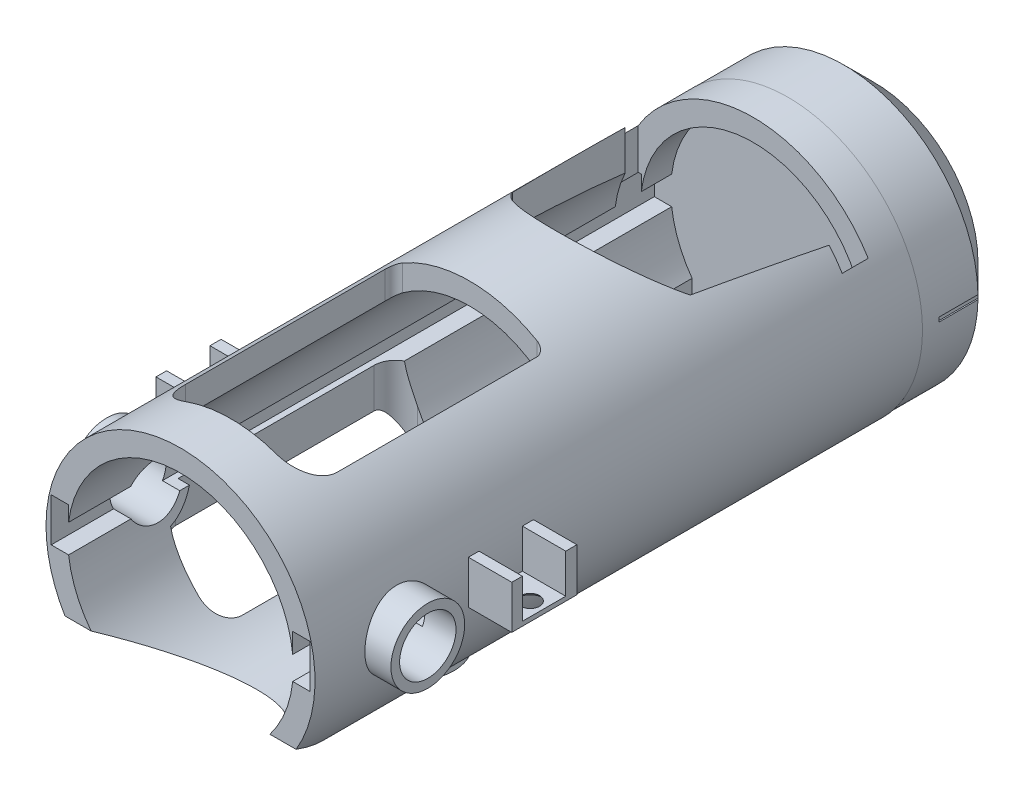
SolidWorks part; units mm, degrees
material "PET"
ref_plane "Front Plane" through (0, 0, 0) normal (0, 0, 1) x (1, 0, 0)
ref_plane "Top Plane" through (0, 0, 0) normal (0, 1, 0) x (1, 0, 0)
ref_plane "Right Plane" through (0, 0, 0) normal (1, 0, 0) x (0, 0, -1)
sketch "Sketch1" plane through (0, 0, 0) normal (0, 0, 1) x (1, 0, 0)
  circle A0 centre (0, 0) radius 31
  dimension "D1" = 62
extrude "Boss-Extrude1" add sketch "Sketch1" along normal blind 140
sketch "Sketch3" plane through (0, 0, 0) normal (0, 1, 0) x (1, 0, 0)
  line L0 (31, 0) -> (-31, 0) construction
  line L1 (-21.0968, 0) -> (20.9032, 0)
  line L2 (-21.0968, 0) -> (-21.0968, -42)
  line L3 (-11.0968, -52) -> (10.9032, -52)
  line L4 (20.9032, 0) -> (20.9032, -42)
  line L5 (-21.0968, 0) -> (20.9032, -52) construction
  line L6 (-21.0968, -52) -> (20.9032, 0) construction
  arc A0 (10.9032, -52) -> (20.9032, -42) centre (10.9032, -42) ccw
  arc A1 (-21.0968, -42) -> (-11.0968, -52) centre (-11.0968, -42) ccw
  point P0 (-0.0968, -26)
  dimension "D3" = 10
  dimension "D1" = 42
  dimension "D2" = 42
extrude "Cut-Extrude3" cut sketch "Sketch3" against normal blind 160
sketch "Sketch4" plane through (0, 0, 0) normal (0, 1, 0) x (1, 0, 0)
  line L0 (10.9032, -52) -> (-11.0968, -52) construction
  circle A0 centre (0, -87) radius 10
  dimension "D1" = 35
extrude "Boss-Extrude2" add sketch "Sketch4" against normal blind 35
sketch "Sketch5" plane through (0, -35, 0) normal (0, -1, 0) x (1, 0, 0)
  circle A0 centre (0, 87) radius 9
extrude "Cut-Extrude4" cut sketch "Sketch5" against normal blind 49
sketch "Sketch6" plane through (0, 0, 0) normal (0, 1, 0) x (1, 0, 0)
  line L1 (-23.4267, -117.7734) -> (-18, -117.7734)
  line L2 (-28.4267, -112.7734) -> (-28.4267, -67)
  line L3 (-23.4267, -62) -> (-18, -62)
  line L4 (-13, -112.7734) -> (-13, -67)
  line L5 (-28.4267, -117.7734) -> (-13, -62) construction
  line L6 (-28.4267, -62) -> (-13, -117.7734) construction
  circle A0 centre (0, -87) radius 10 construction
  arc A1 (-28.4267, -67) -> (-23.4267, -62) centre (-23.4267, -67) cw
  arc A2 (-18, -62) -> (-13, -67) centre (-18, -67) cw
  arc A3 (-18, -117.7734) -> (-13, -112.7734) centre (-18, -112.7734) ccw
  arc A4 (-23.4267, -117.7734) -> (-28.4267, -112.7734) centre (-23.4267, -112.7734) cw
  point P0 (-20.7133, -89.8867)
  dimension "D3" = 5
  dimension "D1" = 13
  dimension "D2" = 10
extrude "Cut-Extrude5" cut sketch "Sketch6" against normal blind 49
sketch "Sketch7" plane through (0, 0, 0) normal (0, 1, 0) x (1, 0, 0)
  line L1 (-15.5, -73.3534) -> (15.5, -73.3534)
  line L2 (-17.5, -75.3534) -> (-17.5, -121.3534)
  line L3 (-10.5, -128.3534) -> (10.5, -128.3534)
  line L4 (17.5, -75.3534) -> (17.5, -121.3534)
  line L5 (-17.5, -73.3534) -> (17.5, -128.3534) construction
  line L6 (-17.5, -128.3534) -> (17.5, -73.3534) construction
  arc A0 (10.5, -128.3534) -> (17.5, -121.3534) centre (10.5, -121.3534) ccw
  arc A1 (-17.5, -121.3534) -> (-10.5, -128.3534) centre (-10.5, -121.3534) ccw
  arc A2 (15.5, -73.3534) -> (17.5, -75.3534) centre (15.5, -75.3534) cw
  arc A3 (-15.5, -73.3534) -> (-17.5, -75.3534) centre (-15.5, -75.3534) ccw
  point P0 (0, -100.8534)
  dimension "D2" = 7
  dimension "D3" = 2
  dimension "D1" = 35
  dimension "D4" = 55
  dimension "D5" = 35
extrude "Cut-Extrude6" cut sketch "Sketch7" along normal blind 100
sketch "Sketch8" plane through (0, 0, 0) normal (0, 1, 0) x (1, 0, 0)
  line L0 (-26.5, -8) -> (26.5, -8)
  line L1 (26.5, -8) -> (26.5, -14)
  line L2 (26.5, -14) -> (23.5, -14)
  line L3 (23.5, -14) -> (20.5, -43)
  line L4 (-20.5, -43) -> (-23.5, -14)
  line L5 (-23.5, -14) -> (-26.5, -14)
  line L6 (-26.5, -14) -> (-26.5, -8)
  line L7 (31, 0) -> (-31, 0) construction
  arc A0 (20.5, -43) -> (-20.5, -43) centre (0, -28) cw
  point P3 (0, -8)
  dimension "D1" = 3
  dimension "D2" = 3
  dimension "D3" = 6
  dimension "D4" = 8
  dimension "D5" = 53
  dimension "D6" = 41
  dimension "D7" = 20
  dimension "D8" = 29
  dimension "D9" = 29
  dimension "D10" = 6
extrude "Cut-Extrude7" cut sketch "Sketch8" along normal blind 77
sketch "Sketch11" plane through (0, 0, 0) normal (1, 0, 0) x (0, 0, -1)
  line L0 (-140, 31) -> (-140, -31) construction
  circle A0 centre (-120, 0) radius 8.5
  dimension "D1" = 20
  dimension "D2" = 17
extrude "Boss-Extrude3" add sketch "Sketch11" against normal blind 37 and the other way blind 37
sketch "Sketch12" plane through (-37, 0, 0) normal (-1, 0, 0) x (0, 0, 1)
  circle A0 centre (120, 0) radius 6.5
  circle A1 centre (120, 0) radius 8.5 construction
  dimension "D1" = 2
extrude "Cut-Extrude10" cut sketch "Sketch12" against normal blind 117
ref_plane "Plane2" through (0, 0, 65) normal (0, 0, 1) x (1, 0, 0)
sketch "Sketch20" plane through (0, 0, 140) normal (0, 0, 1) x (1, 0, 0)
  circle A0 centre (0, 0) radius 26
  arc A1 (-29.8119, 8.5) -> (-29.8119, -8.5) centre (0, 0) ccw construction
  dimension "D1" = 5
extrude "Cut-Extrude13" cut sketch "Sketch20" against normal blind 139
sketch "Sketch21" plane through (0, 0, 140) normal (0, 0, 1) x (1, 0, 0)
  line L1 (-29.796, 6.7498) -> (-25.796, 6.7498)
  line L2 (-29.796, 6.7498) -> (-29.796, -3.2502)
  line L3 (-29.796, -3.2502) -> (-25.796, -3.2502)
  line L4 (-25.796, 6.7498) -> (-25.796, -3.2502)
  line L5 (-29.796, 6.7498) -> (-25.796, -3.2502) construction
  line L6 (-29.796, -3.2502) -> (-25.796, 6.7498) construction
  line L7 (29.86, 7.3057) -> (25.86, 7.3057)
  line L8 (29.86, 7.3057) -> (29.86, -2.6943)
  line L9 (29.86, -2.6943) -> (25.86, -2.6943)
  line L10 (25.86, 7.3057) -> (25.86, -2.6943)
  line L11 (29.86, 7.3057) -> (25.86, -2.6943) construction
  line L12 (29.86, -2.6943) -> (25.86, 7.3057) construction
  arc A0 (20.9032, -15.4614) -> (-21.0968, -15.1962) centre (0, 0) ccw construction
  circle A1 centre (0, 0) radius 26 construction
  point P0 (-27.796, 1.7498)
  point P9 (27.86, 2.3057)
  dimension "D1" = 4
  dimension "D2" = 10
  dimension "D3" = 10
  dimension "D4" = 4
extrude "Cut-Extrude14" cut sketch "Sketch21" against normal blind 139
ref_plane "Plane3" through (0, 0, 0) normal (0, 0, 1) x (1, 0, 0)
sketch "Sketch31" plane through (0, 0, 0) normal (0, 0, 1) x (1, 0, 0)
  line L0 (20.9032, 0) -> (-21.0968, 0) construction
  circle A0 centre (-0.0968, 0) radius 30.9032
extrude "Boss-Extrude5" add sketch "Sketch31" along normal blind 1 and the other way blind 20
chamfer "Chamfer1" distance 7 angle 45 1 edges at (30.8064, 0, -20)
sketch "Sketch32" plane through (0, 0, -20) normal (0, 0, -1) x (-1, 0, 0)
  line L2 (-5, -4.5438) -> (5, -4.5438)
  line L3 (-2.5, -9.981) -> (2.5, -9.981)
  line L4 (-5, -4.5438) -> (-2.5, -9.981)
  line L5 (5, -4.5438) -> (2.5, -9.981)
  point P4 (0, -4.5438)
  point P6 (0, -9.981)
  dimension "D1" = 10
  dimension "D2" = 5
extrude "Boss-Extrude6" add sketch "Sketch32" along normal blind 4
sketch "Sketch33" plane through (0, 0, -24) normal (0, 0, -1) x (-1, 0, 0)
  line L0 (-2.5, -9.981) -> (2.5, -9.981) construction
  line L1 (-2.5, -9.981) -> (2.5, -9.981)
  arc A0 (2.5, -9.981) -> (-2.5, -9.981) centre (0, -8.2563) cw
extrude "Boss-Extrude7" add sketch "Sketch33" along normal blind 4 and the other way blind 5
sketch "Sketch34" plane through (0, 0, -24) normal (0, 0, -1) x (-1, 0, 0)
  line L0 (-3.6409, -5.1794) -> (3.5384, -5.1794)
  line L1 (3.5384, -5.1794) -> (1.6923, -9.981)
  line L2 (-2.5, -9.981) -> (2.5, -9.981) construction
  line L3 (2.5, -9.981) -> (-2.5, -9.981) construction
  line L4 (-1.6923, -9.981) -> (-3.6409, -5.1794)
  arc A0 (1.6923, -9.981) -> (-1.6923, -9.981) centre (0, -9.3303) cw
extrude "Cut-Extrude15" cut sketch "Sketch34" against normal blind 4 and the other way blind 4
ref_plane "Plane4" through (0, -3, 0) normal (0, 1, 0) x (1, 0, 0)
sketch "Sketch35" plane through (0, -3, 0) normal (0, 1, 0) x (1, 0, 0)
  line L0 (-31, 0) -> (-31, -111.5001) construction
  line L8 (-41, -89.6468) -> (-31, -89.6468)
  line L9 (-41, -89.6468) -> (-41, -104.6468)
  line L10 (-41, -104.6468) -> (-31, -104.6468)
  line L11 (-31, -89.6468) -> (-31, -104.6468)
  line L12 (-41, -89.6468) -> (-31, -104.6468) construction
  line L13 (-41, -104.6468) -> (-31, -89.6468) construction
  line L14 (31, -111.5001) -> (31, 0) construction
  line L21 (41, -104.6468) -> (31, -104.6468)
  line L22 (41, -104.6468) -> (41, -89.6468)
  line L23 (41, -89.6468) -> (31, -89.6468)
  line L24 (31, -104.6468) -> (31, -89.6468)
  line L25 (41, -104.6468) -> (31, -89.6468) construction
  line L26 (41, -89.6468) -> (31, -104.6468) construction
  point P7 (-36, -97.1468)
  point P12 (36, -97.1468)
  dimension "D2" = 15
  dimension "D6" = 10
extrude "Boss-Extrude8" add sketch "Sketch35" along normal blind 10 separate body
sketch "Sketch36" plane through (0, 7, 0) normal (0, 1, 0) x (1, 0, 0)
  line L0 (41, -104.6468) -> (41, -89.6468) construction
  line L1 (31, -92.2089) -> (41, -92.2089)
  line L2 (31, -92.2089) -> (31, -102.2089)
  line L3 (31, -102.2089) -> (41, -102.2089)
  line L4 (41, -92.2089) -> (41, -102.2089)
  line L5 (31, -92.2089) -> (41, -102.2089) construction
  line L6 (31, -102.2089) -> (41, -92.2089) construction
  line L7 (-31, -104.6468) -> (-31, -89.6468) construction
  line L8 (-41, -92.2089) -> (-31, -92.2089)
  line L9 (-41, -92.2089) -> (-41, -102.2089)
  line L10 (-41, -102.2089) -> (-31, -102.2089)
  line L11 (-31, -92.2089) -> (-31, -102.2089)
  line L12 (-41, -92.2089) -> (-31, -102.2089) construction
  line L13 (-41, -102.2089) -> (-31, -92.2089) construction
  point P0 (36, -97.2089)
  point P7 (-36, -97.2089)
  dimension "D1" = 10
extrude "Cut-Extrude16" cut sketch "Sketch36" against normal blind 9
hole_wizard "CSK for M3 Countersunk Flat Head Screw1" positions "3DSketch1" profile "Sketch37" countersink size "M3" standard "ISO"
sketch3d "3DSketch1"
  point P0 (-37.8547, -3, 96.9875)
  point P2 (37.8547, -3, 97.2486)
sketch "Sketch37" plane through (-37.8547, -3, 96.9875) normal (1, 0, 0) x (0, 0, -1)
  line L0 (0, 0) -> (0, 34)
  line L1 (0, 34) -> (1.7, 34)
  line L2 (1.7, 34) -> (1.7, 1.45)
  line L3 (1.7, 1.45) -> (3.15, 0)
  line L5 (3.15, 0) -> (0, 0)
  line L6 (-1.7, 1.45) -> (-3.15, 0) construction
  line L11 (0, -6.35) -> (0, 107.95) construction
  dimension "Thru Hole Dia." = 3.4
  dimension "Thru Hole Depth" = 34
  dimension "Near C'Sink Dia." = 6.3
  dimension "Near C'Sink Angle" = 90
sketch "Sketch39" plane through (0, 0, -20) normal (0, 0, -1) x (-1, 0, 0)
  line L0 (31, 7) -> (31, -3) construction
  line L1 (-31.5, 0.5) -> (-30.5, 0.5)
  line L2 (-31.5, 0.5) -> (-31.5, -0.5)
  line L3 (-31.5, -0.5) -> (-30.5, -0.5)
  line L4 (-30.5, 0.5) -> (-30.5, -0.5)
  line L5 (-31.5, 0.5) -> (-30.5, -0.5) construction
  line L6 (-31.5, -0.5) -> (-30.5, 0.5) construction
  line L7 (30.5, 0.5) -> (31.5, 0.5)
  line L8 (30.5, 0.5) -> (30.5, -0.5)
  line L9 (30.5, -0.5) -> (31.5, -0.5)
  line L10 (31.5, 0.5) -> (31.5, -0.5)
  line L11 (30.5, 0.5) -> (31.5, -0.5) construction
  line L12 (30.5, -0.5) -> (31.5, 0.5) construction
  arc A0 (-29.8119, 8.5) -> (-29.8119, -8.5) centre (0, 0) ccw construction
  circle A1 centre (0.0968, 0) radius 30.9032 construction
  point P0 (-31, 0)
  point P8 (31, 0)
  dimension "D1" = 1
  dimension "D2" = 1
  dimension "D3" = 1
  dimension "D4" = 1
extrude "Cut-Extrude19" cut sketch "Sketch39" against normal blind 16
sketch "Sketch40" plane through (0, 0, 140) normal (0, 0, 1) x (1, 0, 0)
  line L0 (-27.1789, -15.8567) -> (31.1789, -15.8567) construction
ref_plane "Plane6" through (0, -72.5143, 41.8662) normal (0, -0.866, 0.5) x (1, 0, 0)
sketch "Sketch41" plane through (0, -72.5143, 41.8662) normal (0, -0.866, 0.5) x (1, 0, 0)
  line L1 (-34.8478, 139.5327) -> (36.7155, 139.5327)
  line L2 (-34.8478, 139.5327) -> (-34.8478, 84.0609)
  line L3 (-34.8478, 84.0609) -> (36.7155, 84.0609)
  line L4 (36.7155, 139.5327) -> (36.7155, 84.0609)
  line L5 (-34.8478, 139.5327) -> (36.7155, 84.0609) construction
  line L6 (-34.8478, 84.0609) -> (36.7155, 139.5327) construction
  point P0 (0.9338, 111.7968)
extrude "Cut-Extrude20" cut sketch "Sketch41" along normal blind 45
equation "\"45..00mm\"=39"
